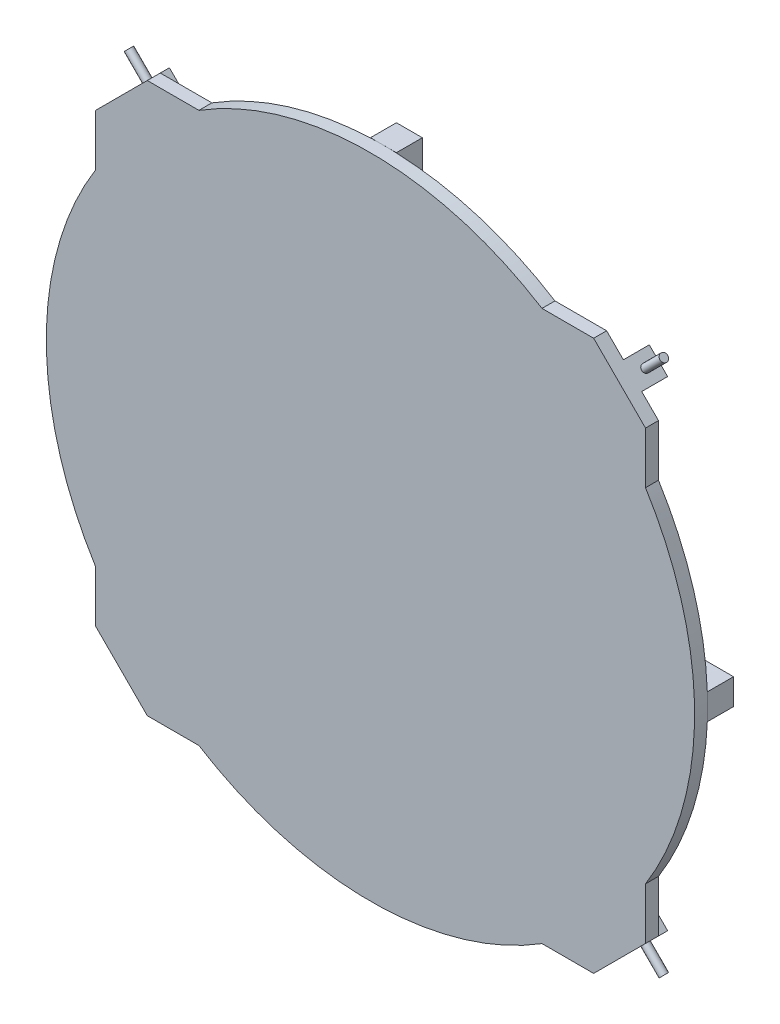
SolidWorks part; units mm, degrees
ref_plane "Front Plane" through (0, 0, 0) normal (0, 0, 1) x (1, 0, 0)
ref_plane "Top Plane" through (0, 0, 0) normal (0, 1, 0) x (1, 0, 0)
ref_plane "Right Plane" through (0, 0, 0) normal (1, 0, 0) x (0, 0, -1)
sketch "Sketch1" plane through (0, 0, 0) normal (0, 0, 1) x (1, 0, 0)
  line L0 (0, 28.4652) -> (0, -28.3669) construction
  line L1 (-32.0541, 0) -> (29.1043, 0) construction
  line L2 (0, 0) -> (212.132, 212.132) construction
  line L3 (0, 0) -> (212.132, -212.132) construction
  line L4 (0, 0) -> (-212.132, -212.132) construction
  line L5 (0, 0) -> (-212.132, 212.132) construction
  line L6 (-172.132, 212.132) -> (-132.2876, 212.132)
  line L7 (-212.132, 172.132) -> (-212.132, 132.2876)
  line L8 (212.132, 172.132) -> (212.132, 132.2876)
  line L9 (-172.132, -212.132) -> (-132.2876, -212.132)
  line L10 (132.2876, 212.132) -> (172.132, 212.132)
  line L11 (-212.132, -132.2876) -> (-212.132, -172.132)
  line L12 (212.132, -132.2876) -> (212.132, -172.132)
  line L13 (132.2876, -212.132) -> (172.132, -212.132)
  line L14 (-212.132, 172.132) -> (-172.132, 212.132)
  line L15 (172.132, 212.132) -> (212.132, 172.132)
  line L16 (212.132, -172.132) -> (172.132, -212.132)
  line L17 (-212.132, -172.132) -> (-172.132, -212.132)
  arc A0 (-212.132, 132.2876) -> (-212.132, -132.2876) centre (0, 0) ccw
  arc A1 (132.2876, 212.132) -> (-132.2876, 212.132) centre (0, 0) ccw
  arc A2 (212.132, -132.2876) -> (212.132, 132.2876) centre (0, 0) ccw
  arc A3 (-132.2876, -212.132) -> (132.2876, -212.132) centre (0, 0) ccw
  point P14 (0, 0)
  dimension "D1" = 500
  dimension "D2" = 45
  dimension "D3" = 300
  dimension "D4" = 4
extrude "Boss-Extrude2" add sketch "Sketch1" along normal blind 10 contours A0 L11 L17 L9 A3 L13 L16 L12 A2 L8 L15 L10 A1 L6 L14 L7
sketch "Sketch2" plane through (0, 0, 0) normal (0, 0, -1) x (-1, 0, 0)
  line L0 (10, 10) -> (192.132, 192.132) construction
  line L1 (10, 250) -> (-10, 250)
  line L2 (10, 250) -> (10, 24.1421)
  line L3 (10, -249.7999) -> (-10, -249.7999)
  line L4 (-10, 250) -> (-10, 24.1421)
  line L5 (0, 250) -> (0, 0) construction
  line L6 (-199.2031, 185.061) -> (-185.061, 199.2031)
  line L7 (-250, 10) -> (-24.1421, 10)
  line L8 (-250, 10) -> (-250, -10)
  line L9 (-250, -10) -> (-24.1421, -10)
  line L10 (249.7999, 10) -> (249.7999, -10)
  line L11 (212.132, 172.132) -> (172.132, 212.132) construction
  line L12 (192.132, 192.132) -> (185.061, 199.2031)
  line L13 (185.061, 199.2031) -> (10, 24.1421)
  line L14 (-10, -24.1421) -> (-10, -249.7999)
  line L15 (10, -24.1421) -> (10, -249.7999)
  line L16 (24.1421, 10) -> (249.7999, 10)
  line L17 (-0.4003, 10) -> (0.4003, 10)
  line L18 (199.2031, 185.061) -> (24.1421, 10)
  line L19 (24.1421, -10) -> (249.7999, -10)
  line L20 (185.061, -199.2031) -> (10, -24.1421)
  line L21 (10, -10) -> (192.132, -192.132) construction
  line L22 (199.2031, -185.061) -> (24.1421, -10)
  line L23 (-199.2031, -185.061) -> (-24.1421, -10)
  line L24 (-10, -10) -> (-192.132, -192.132) construction
  line L25 (-185.061, -199.2031) -> (-10, -24.1421)
  line L26 (-185.061, 199.2031) -> (-10, 24.1421)
  line L27 (-10, 10) -> (-192.132, 192.132) construction
  line L28 (-199.2031, 185.061) -> (-24.1421, 10)
  line L29 (192.132, 192.132) -> (199.2031, 185.061)
  line L30 (199.2031, -185.061) -> (185.061, -199.2031)
  line L31 (-199.2031, -185.061) -> (-185.061, -199.2031)
  arc A0 (-132.2876, -212.132) -> (132.2876, -212.132) centre (0, 0) ccw construction
  arc A1 (212.132, -132.2876) -> (212.132, 132.2876) centre (0, 0) ccw construction
  arc A2 (-212.132, 132.2876) -> (-212.132, -132.2876) centre (0, 0) ccw construction
  arc A3 (132.2876, 212.132) -> (-132.2876, 212.132) centre (0, 0) ccw construction
  point P0 (0, 0)
  point P9 (0, 0)
  point P51 (0, 0)
  dimension "D1" = 20
  dimension "D3" = 10
  dimension "D4" = 45
  dimension "D5" = 10
  dimension "D6" = 4
extrude "Boss-Extrude3" add sketch "Sketch2" along normal blind 20 contours L25 L14 L3 L15 L20 L30 L22 L19 L10 L16 L18 L29 L12 L13 L2 L1 L4 L26 L6 L28 L7 L8 L9 L23 L31
sketch "Sketch3" plane through (192.132, 192.132, 0) normal (0.7071, 0.7071, 0) x (0, 0, -1)
  line L0 (-10, 0) -> (20, 0) construction
  line L1 (-10, 28.2843) -> (-10, -28.2843) construction
  line L2 (20, -10) -> (20, 10) construction
  line L3 (10, 10) -> (10, -10) construction
  line L4 (20, 10) -> (0, 10) construction
  line L5 (20, -10) -> (0, -10) construction
  circle A0 centre (9.9772, 0) radius 3
  dimension "D1" = 6
extrude "Boss-Extrude4" add sketch "Sketch3" along normal blind 20
sketch "Sketch4" plane through (-192.132, 192.132, 0) normal (-0.7071, 0.7071, 0) x (0, 0, 1)
  line L0 (-20, 0) -> (10, 0) construction
  line L1 (-20, 10) -> (-20, -10) construction
  line L2 (10, -28.2843) -> (10, 28.2843) construction
  line L3 (-10, 10) -> (-10, -10) construction
  line L4 (-20, 10) -> (0, 10) construction
  line L5 (-20, -10) -> (0, -10) construction
  circle A0 centre (-10, 0) radius 3
  dimension "D1" = 6
sketch "Sketch5" plane through (-192.132, -192.132, 0) normal (-0.7071, -0.7071, 0) x (0, 0, 1)
  line L0 (-20, 0) -> (10, 0) construction
  line L1 (-20, 10) -> (-20, -10) construction
  line L2 (10, 28.2843) -> (10, -28.2843) construction
  line L3 (-10, 10) -> (-10, -10) construction
  line L4 (-20, 10) -> (0, 10) construction
  line L5 (-20, -10) -> (0, -10) construction
  circle A0 centre (-10, 0) radius 3
  dimension "D1" = 6
extrude "Boss-Extrude5" add sketch "Sketch4" along normal blind 20 contours A0
extrude "Boss-Extrude6" add sketch "Sketch5" along normal blind 20 contours A0
sketch "Sketch8" plane through (192.132, -192.132, 0) normal (0.7071, -0.7071, 0) x (0, 0, -1)
  line L0 (-10, 0) -> (20, 0) construction
  line L1 (-10, 28.2843) -> (-10, -28.2843) construction
  line L2 (20, 10) -> (20, -10) construction
  line L3 (10, 10) -> (10, -10) construction
  line L4 (20, 10) -> (0, 10) construction
  line L5 (20, -10) -> (0, -10) construction
  circle A0 centre (10, 0) radius 3
  dimension "D1" = 6
extrude "Boss-Extrude7" add sketch "Sketch8" along normal blind 20
